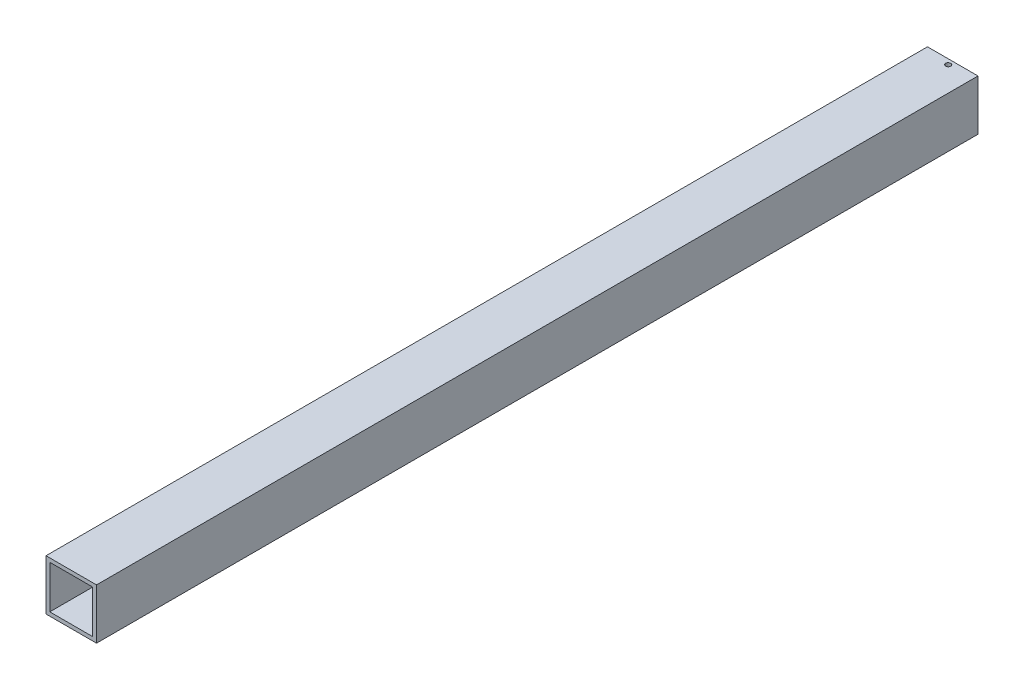
SolidWorks part; units mm, degrees
ref_plane "Płaszczyzna przednia" through (0, 0, 0) normal (0, 0, 1) x (1, 0, 0)
ref_plane "Płaszczyzna górna" through (0, 0, 0) normal (0, 1, 0) x (1, 0, 0)
ref_plane "Płaszczyzna prawa" through (0, 0, 0) normal (1, 0, 0) x (0, 0, -1)
sketch "Szkic1" plane through (0, 0, 0) normal (0, 0, 1) x (1, 0, 0)
  line L2 (-30.423, 18.5) -> (-30.423, -1.5)
  line L3 (-30.423, -1.5) -> (-10.423, -1.5)
  line L4 (-10.423, 18.5) -> (-10.423, -1.5)
  line L8 (-30.423, 18.5) -> (-10.423, 18.5)
  line L10 (-28.923, 17) -> (-11.923, 17)
  line L11 (-28.923, 17) -> (-28.923, 0)
  line L12 (-28.923, 0) -> (-11.923, 0)
  line L13 (-11.923, 17) -> (-11.923, 0)
  dimension "D1" = 20
  dimension "D2" = 20
  dimension "D3" = 1.5
  dimension "D4" = 1.5
  dimension "D5" = 1.5
  dimension "D6" = 1.5
extrude "Dodanie-wyciągnięcie1" add sketch "Szkic1" along normal up to surface (349 mm away)
sketch "Szkic3" plane through (0, 18.5, 0) normal (0, 1, 0) x (1, 0, 0)
  circle A0 centre (-20.1716, -2.0464) radius 1
extrude "Wytnij-wyciągnięcie1" cut sketch "Szkic3" against normal through all
